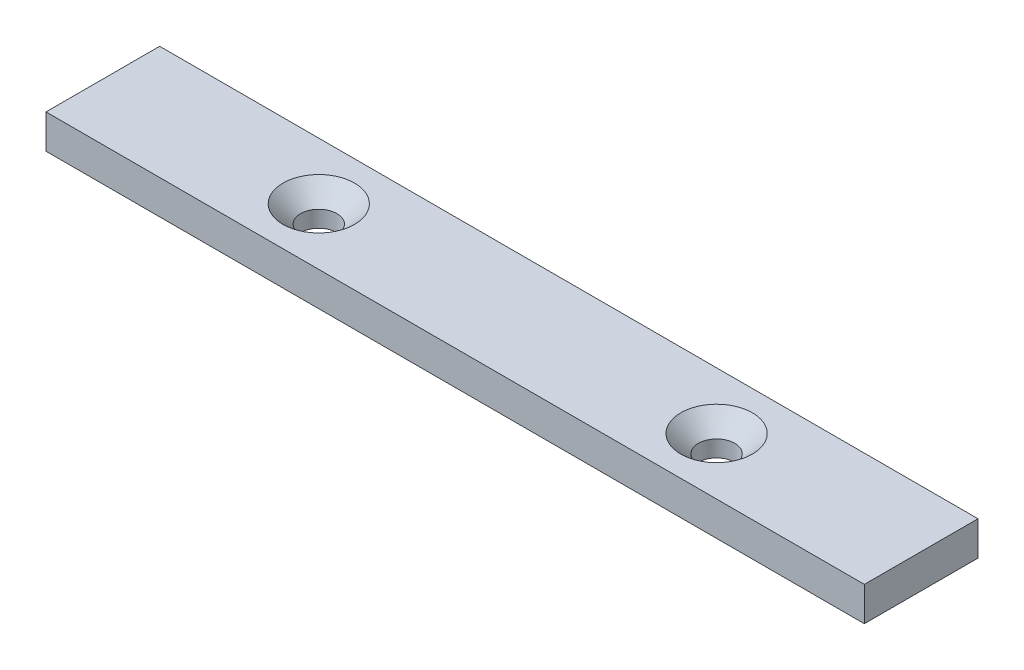
SolidWorks part; units mm, degrees
ref_plane "Front Plane" through (0, 0, 0) normal (0, 0, 1) x (1, 0, 0)
ref_plane "Top Plane" through (0, 0, 0) normal (0, 1, 0) x (1, 0, 0)
ref_plane "Right Plane" through (0, 0, 0) normal (1, 0, 0) x (0, 0, -1)
sketch "Sketch1" plane through (0, 0, 0) normal (0, 1, 0) x (1, 0, 0)
  line L1 (-72, -10) -> (72, -10)
  line L2 (-72, -10) -> (-72, 10)
  line L3 (-72, 10) -> (72, 10)
  line L4 (72, -10) -> (72, 10)
  line L5 (-72, -10) -> (72, 10) construction
  line L6 (-72, 10) -> (72, -10) construction
  point P0 (0, 0)
  dimension "D1" = 144
  dimension "D2" = 20
extrude "Boss-Extrude1" add sketch "Sketch1" along normal blind 6
hole_wizard "CSK for M6 Flat Head Machine Screw1" positions "Sketch2" profile "Sketch3" countersink size "M6" standard "ANSI Metric" end condition up to next
sketch "Sketch2" plane through (0, 6, 0) normal (0, 1, 0) x (1, 0, 0)
  line L0 (-72, 10) -> (-72, -10) construction
  point P0 (36, 0)
  point P2 (-34, 0)
  dimension "D1" = 70
  dimension "D2" = 38
sketch "Sketch3" plane through (36, 6, 0) normal (1, 0, 0) x (0, 0, 1)
  line L0 (0, 0) -> (0, 6)
  line L1 (0, 6) -> (3.2, 6)
  line L2 (3.2, 6) -> (3.2, 3.1)
  line L3 (3.2, 3.1) -> (6.3, 0)
  line L5 (6.3, 0) -> (0, 0)
  line L6 (-3.2, 3.1) -> (-6.3, 0) construction
  line L11 (0, -6.35) -> (0, 107.95) construction
  dimension "Thru Hole Dia." = 6.4
  dimension "Thru Hole Depth" = 6
  dimension "Near C'Sink Dia." = 12.6
  dimension "Near C'Sink Angle" = 90
